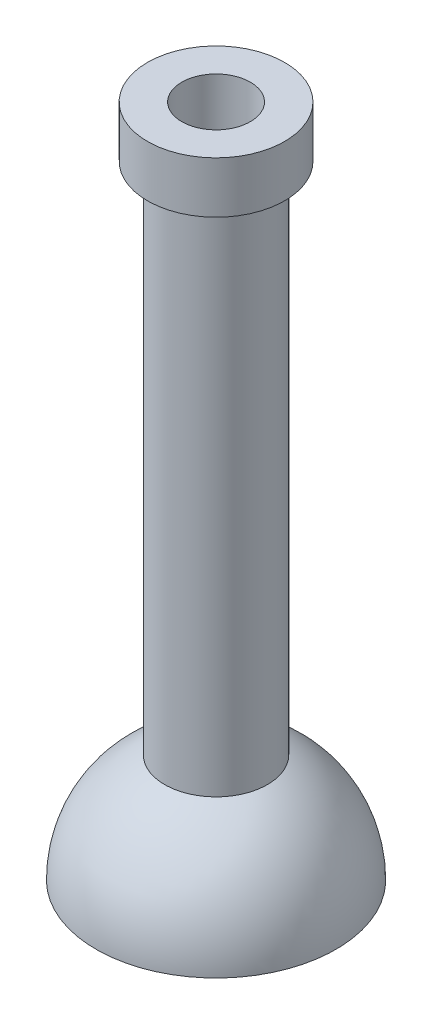
SolidWorks part; units mm, degrees
ref_plane "Front Plane" through (0, 0, 0) normal (0, 0, 1) x (1, 0, 0)
ref_plane "Top Plane" through (0, 0, 0) normal (0, 1, 0) x (1, 0, 0)
ref_plane "Right Plane" through (0, 0, 0) normal (1, 0, 0) x (0, 0, -1)
sketch "Sketch1" plane through (0, 0, 0) normal (0, 0, 1) x (1, 0, 0)
  line L0 (0, 0) -> (0, -30)
  line L3 (0, 0) -> (4, 0)
  line L4 (4, 0) -> (4, -3)
  line L5 (4, -3) -> (3, -3)
  line L6 (3, -3) -> (3, -33)
  line L9 (0, -30) -> (0, -34.3246)
  line L12 (0, -46.3246) -> (7, -46.3246) construction
  line L13 (0, -44.3246) -> (5, -44.3246) construction
  line L14 (7, -39.3246) -> (7, -46.3246) construction
  line L15 (5, -39.3246) -> (5, -44.3246) construction
  line L16 (0, -34.3246) -> (0, -39.3246)
  line L20 (5, -39.3246) -> (7, -39.3246)
  arc A1 (7, -39.3246) -> (3, -33) centre (0, -39.3246) ccw
  arc A2 (5, -39.3246) -> (0, -34.3246) centre (0, -39.3246) ccw
  arc A3 (7, -39.3246) -> (0, -46.3246) centre (0, -39.3246) ccw construction
  arc A4 (5, -39.3246) -> (0, -44.3246) centre (0, -39.3246) ccw construction
  dimension "D6" = 5
  dimension "D2" = 3
  dimension "D3" = 4
  dimension "D4" = 30
  dimension "D5" = 3
  dimension "D1" = 2
revolve "Revolve1" add sketch "Sketch1" angle 360 about L0
sketch "Sketch2" plane through (0, 0, 0) normal (0, 1, 0) x (1, 0, 0)
  circle A0 centre (0, 0) radius 2
  dimension "D1" = 4
extrude "Cut-Extrude1" cut sketch "Sketch2" against normal through all
